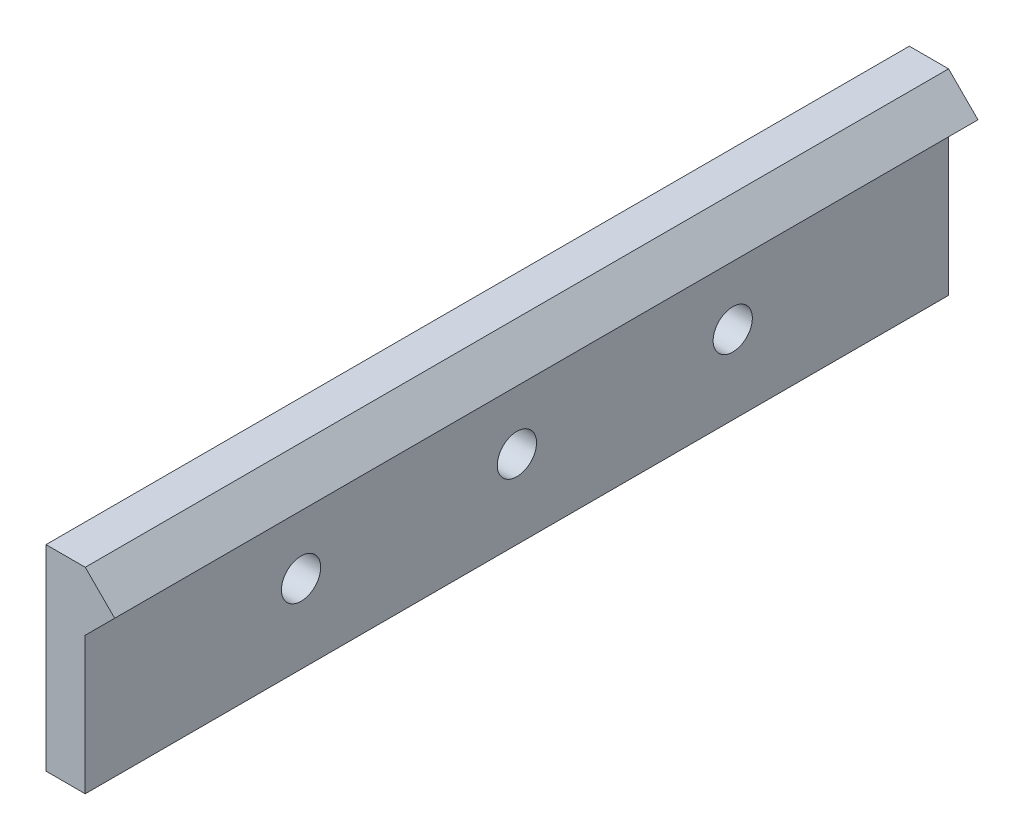
SolidWorks part; units mm, degrees
ref_plane "Front Plane" through (0, 0, 0) normal (0, 0, 1) x (1, 0, 0)
ref_plane "Top Plane" through (0, 0, 0) normal (0, 1, 0) x (1, 0, 0)
ref_plane "Right Plane" through (0, 0, 0) normal (1, 0, 0) x (0, 0, -1)
sketch "Sketch1" plane through (0, 0, 0) normal (0, 0, 1) x (1, 0, 0)
  line L0 (-104.5584, 0) -> (104.5584, 0) construction
  line L1 (0, -141.8542) -> (0, 141.8542) construction
  line L2 (6.35, 63.5) -> (15.875, 53.975)
  line L3 (-6.35, 0) -> (6.35, 0)
  line L4 (-6.35, 0) -> (-6.35, 63.5)
  line L5 (-6.35, 63.5) -> (6.35, 63.5)
  line L10 (6.35, 44.45) -> (15.875, 53.975)
  line L11 (6.35, 63.5) -> (6.35, 0) construction
  line L12 (6.35, 44.45) -> (6.35, 0)
  point P4 (0, 0)
  point P8 (0, 0)
  point P16 (6.35, 127)
  dimension "D1" = 6.35
  dimension "D2" = 12.7
  dimension "D3" = 45
  dimension "D4" = 63.5
  dimension "D5" = 44.45
  dimension "D6" = 45
extrude "Boss-Extrude1" add sketch "Sketch1" along normal mid plane 279.4
sketch "Sketch2" plane through (0, 0, 0) normal (1, 0, 0) x (0, 0, -1)
  line L0 (-190.652, 0) -> (190.652, 0) construction
  line L2 (0, -172.5187) -> (0, 172.5187) construction
  circle A0 centre (-69.85, 25.4) radius 6.35
  circle A1 centre (0, 25.4) radius 6.35
  circle A2 centre (69.85, 25.4) radius 6.35
  point P4 (0, 0)
  point P8 (0, 0)
  dimension "D3" = 12.7
  dimension "D1" = 25.4
  dimension "D2" = 69.85
  dimension "D4" = 3
extrude "Cut-Extrude1" cut sketch "Sketch2" against normal mid plane 76.2
